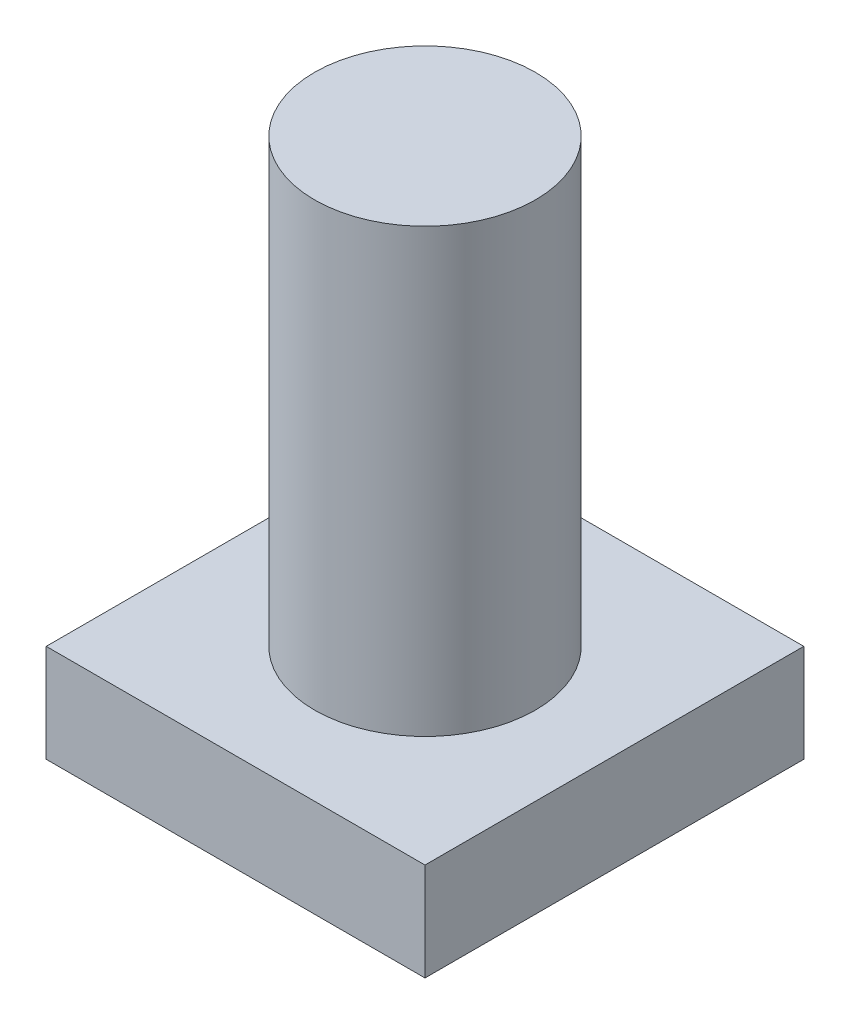
SolidWorks part; units mm, degrees
ref_plane "前视" through (0, 0, 0) normal (0, 0, 1) x (1, 0, 0)
ref_plane "上视" through (0, 0, 0) normal (0, 1, 0) x (1, 0, 0)
ref_plane "右视" through (0, 0, 0) normal (1, 0, 0) x (0, 0, -1)
sketch "草图1" plane through (0, 0, 0) normal (0, 1, 0) x (1, 0, 0)
  line L0 (0, 96.9306) -> (0, -101.3275) construction
  line L1 (-119.7143, 0) -> (134.9034, 0) construction
  line L3 (-6, 6) -> (6, 6)
  line L4 (-6, 6) -> (-6, -6)
  line L5 (-6, -6) -> (6, -6)
  line L6 (6, 6) -> (6, -6)
  dimension "D1" = 12
  dimension "D2" = 12
extrude "拉伸1" add sketch "草图1" along normal blind 3.1
sketch "草图2" plane through (0, 3.1, 0) normal (0, 1, 0) x (-1, 0, 0)
  line L0 (-6, 0) -> (8.7109, 0) construction
  line L1 (-6, 6) -> (-6, -6) construction
  line L2 (0, -7.8518) -> (0, 10.0992) construction
  circle A0 centre (0, 0) radius 3.5
  dimension "D1" = 7
extrude "拉伸2" add sketch "草图2" along normal blind 14
sketch "草图3" plane through (-6, 0, 0) normal (-1, 0, 0) x (0, 0, 1)
  line L0 (0, -6.9925) -> (0, 14.8526) construction
sketch "草图4" plane through (0, 17.1, 0) normal (0, 1, 0) x (-1, 0, 0)
  line L0 (0, -4.1469) -> (0, 4.9476) construction
  line L1 (-3.9082, 0) -> (5.1305, 0) construction
sketch "草图5" plane through (0, 0, 0) normal (0, -1, 0) x (1, 0, 0)
  line L0 (10.1949, 0) -> (-13.2034, 0) construction
  line L1 (0, 8.665) -> (0, -9.2576) construction
